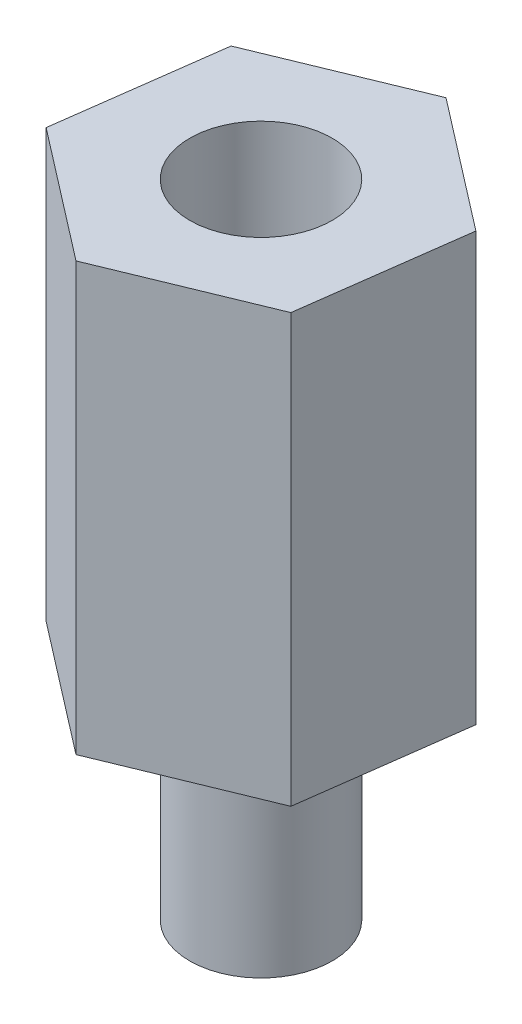
SolidWorks part; units mm, degrees
ref_plane "Front Plane" through (0, 0, 0) normal (0, 0, 1) x (1, 0, 0)
ref_plane "Top Plane" through (0, 0, 0) normal (0, 1, 0) x (1, 0, 0)
ref_plane "Right Plane" through (0, 0, 0) normal (1, 0, 0) x (0, 0, -1)
sketch "Sketch1" plane through (0, 0, 0) normal (0, 1, 0) x (1, 0, 0)
  circle A0 centre (0, 0) radius 1
  dimension "D1" = 2
extrude "Boss-Extrude1" add sketch "Sketch1" along normal blind 3
sketch "Sketch2" plane through (0, 3, 0) normal (0, 1, 0) x (1, 0, 0)
  line L0 (0, 0) -> (6.817, -5.2542) construction
  line L1 (0.191, 1.4268) -> (0.3799, 2.8382) construction
  line L2 (0.6256, 0.2576) -> (-0.9412, -0.3875) construction
  line L3 (-0.3064, -2.2896) -> (1.8296, -1.4102)
  line L4 (1.8296, -1.4102) -> (2.1361, 0.8794)
  line L5 (2.1361, 0.8794) -> (0.3064, 2.2896)
  line L6 (0.3064, 2.2896) -> (-1.8296, 1.4102)
  line L7 (-1.8296, 1.4102) -> (-2.1361, -0.8794)
  line L8 (-2.1361, -0.8794) -> (-0.3064, -2.2896)
  dimension "D1" = 60
  dimension "D2" = 60
  dimension "D3" = 2.31
extrude "Boss-Extrude2" add sketch "Sketch2" along normal blind 6
sketch "Sketch3" plane through (0, 9, 0) normal (0, 1, 0) x (1, 0, 0)
  circle A0 centre (0, 0) radius 1
  dimension "D1" = 2
extrude "Cut-Extrude1" cut sketch "Sketch3" against normal blind 5
